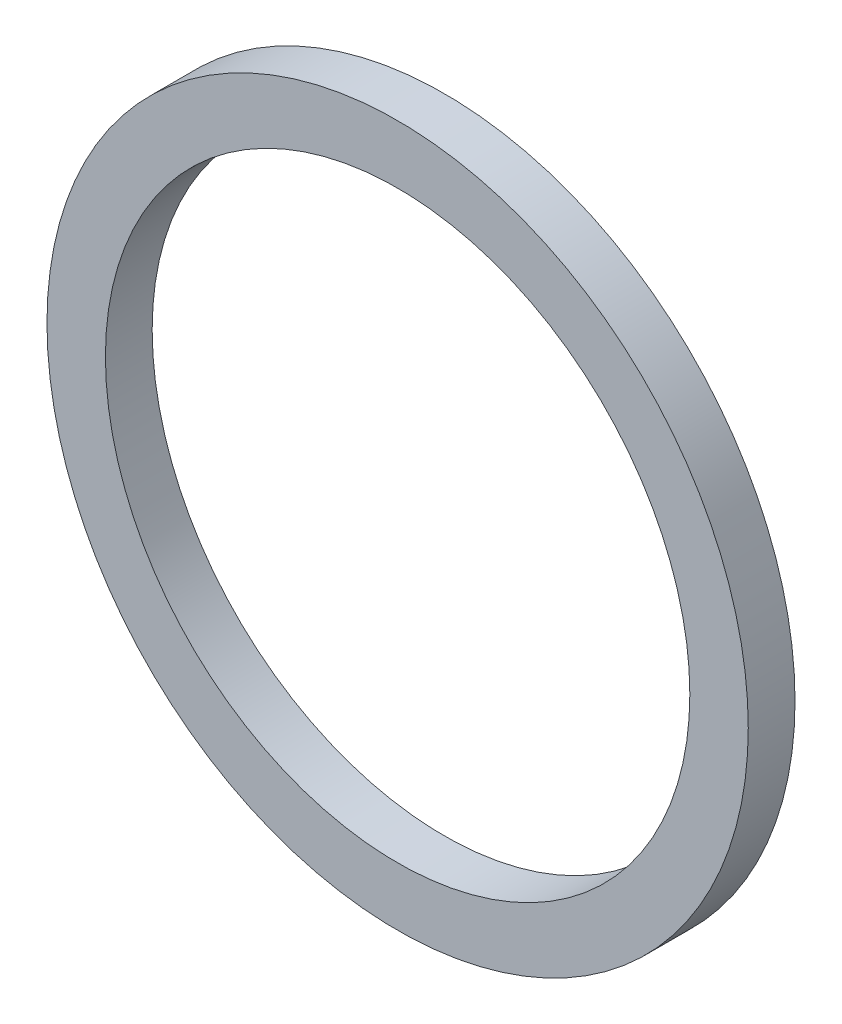
SolidWorks part; units mm, degrees
ref_plane "Přední rovina" through (0, 0, 0) normal (0, 0, 1) x (1, 0, 0)
ref_plane "Horní rovina" through (0, 0, 0) normal (0, 1, 0) x (1, 0, 0)
ref_plane "Pravá rovina" through (0, 0, 0) normal (1, 0, 0) x (0, 0, -1)
sketch "Skica1" plane through (0, 0, 0) normal (0, 0, 1) x (1, 0, 0)
  circle A0 centre (0, 0) radius 5
  circle A1 centre (0, 0) radius 6
  dimension "D1" = 10
  dimension "D2" = 1
extrude "Přidat vysunutím1" add sketch "Skica1" along normal blind 0.8
